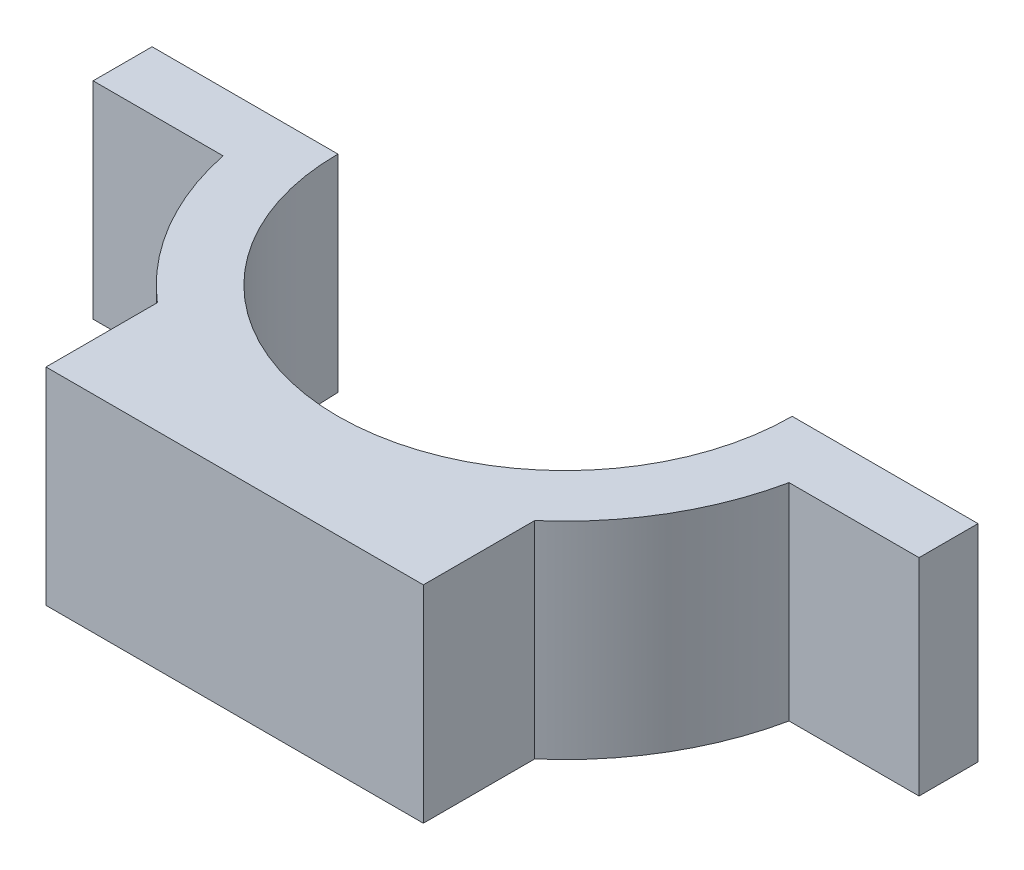
SolidWorks part; units mm, degrees
ref_plane "Front Plane" through (0, 0, 0) normal (0, 0, 1) x (1, 0, 0)
ref_plane "Top Plane" through (0, 0, 0) normal (0, 1, 0) x (1, 0, 0)
ref_plane "Right Plane" through (0, 0, 0) normal (1, 0, 0) x (0, 0, -1)
sketch "Sketch1" plane through (0, 0, 0) normal (0, 1, 0) x (1, 0, 0)
  line L0 (87.0289, 0) -> (-97.3953, 0)
  circle A0 centre (0, 0) radius 70
  circle A1 centre (0, 0) radius 55
  circle A2 centre (0, 0) radius 11.9422
  dimension "D1" = 140
  dimension "D2" = 110
extrude "Boss-Extrude1" add sketch "Sketch1" along normal blind 50 contours A1 L0 A0
sketch "Sketch3" plane through (0, 0, 0) normal (1, 0, 0) x (0, 0, -1)
  line L0 (0, 50) -> (-55, 50) construction
  line L1 (-14.2822, 50) -> (0, 50)
  line L2 (-14.2822, 50) -> (-14.2822, 0)
  line L3 (-14.2822, 0) -> (0, 0)
  line L4 (0, 50) -> (0, 0)
extrude "Boss-Extrude2" add sketch "Sketch3" along normal mid plane 200 contours L4 L3 L2 L1
sketch "Sketch4" plane through (0, 50, 0) normal (0, 1, 0) x (1, 0, 0)
  line L0 (-55, 0) -> (55, 0)
  circle A0 centre (0, 0) radius 55
sketch "Sketch10" plane through (0, 50, 0) normal (0, 1, 0) x (1, 0, 0)
  circle A0 centre (0, 0) radius 55
extrude "Cut-Extrude3" cut sketch "Sketch10" against normal blind 200
sketch "Sketch11" plane through (0, 0, 0) normal (0, 0, 1) x (1, 0, 0)
  line L0 (-68.5275, 0) -> (68.5275, 0) construction
  line L1 (-45.6896, 50) -> (45.6896, 50)
  line L2 (-45.6896, 50) -> (-45.6896, 0)
  line L3 (-45.6896, 0) -> (45.6896, 0)
  line L4 (45.6896, 50) -> (45.6896, 0)
  line L5 (-45.6896, 50) -> (45.6896, 0) construction
  line L6 (-45.6896, 0) -> (45.6896, 50) construction
  point P0 (0, 25)
  dimension "D1" = 50
  dimension "D2" = 25
extrude "Boss-Extrude4" add sketch "Sketch11" along normal blind 80
sketch "Sketch12" plane through (0, 50, 0) normal (0, 1, 0) x (1, 0, 0)
  circle A0 centre (0, 0) radius 55
extrude "Cut-Extrude4" cut sketch "Sketch12" against normal blind 200
sketch "Sketch8" plane through (0, 0, 0) normal (0, 0, 1) x (1, 0, 0)
  line L0 (-68.5275, 0) -> (-45.6896, 0) construction
  line L1 (-40.7866, 50) -> (40.7866, 50)
  line L2 (-40.7866, 50) -> (-40.7866, 0)
  line L3 (-40.7866, 0) -> (40.7866, 0)
  line L4 (40.7866, 50) -> (40.7866, 0)
  line L5 (-40.7866, 50) -> (40.7866, 0) construction
  line L6 (-40.7866, 0) -> (40.7866, 50) construction
  line L7 (-45.6896, 50) -> (-68.5275, 50) construction
  point P0 (0, 25)
  dimension "D1" = 25
